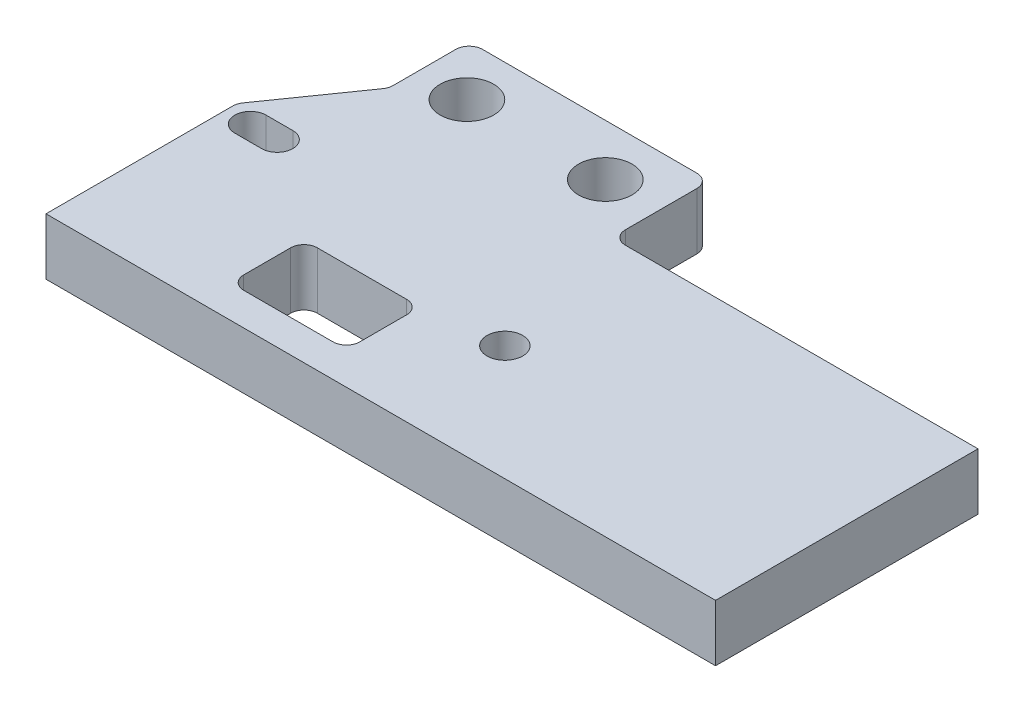
SolidWorks part; units mm, degrees
material "1060 Alloy"
ref_plane "Front Plane" through (0, 0, 0) normal (0, 0, 1) x (1, 0, 0)
ref_plane "Top Plane" through (0, 0, 0) normal (0, 1, 0) x (1, 0, 0)
ref_plane "Right Plane" through (0, 0, 0) normal (1, 0, 0) x (0, 0, -1)
sketch "Sketch1" plane through (0, 0, 0) normal (0, 1, 0) x (1, 0, 0)
  line L0 (38, 0) -> (38, 5)
  line L1 (0, 0) -> (38, 0)
  line L2 (0, 0) -> (0, 48.5)
  line L3 (7, 67.5) -> (34, 67.5)
  line L4 (96, 0) -> (96, 48.5)
  line L5 (0, 48.5) -> (7, 58.5)
  line L6 (7, 58.5) -> (7, 67.5)
  line L7 (34, 67.5) -> (34, 56.5)
  line L8 (48, -139.8616) -> (48, 139.8616) construction
  line L9 (58, 0) -> (58, 5)
  line L10 (96, 48.5) -> (89, 58.5)
  line L11 (89, 58.5) -> (89, 67.5)
  line L12 (62, 67.5) -> (62, 56.5)
  line L13 (38, 5) -> (58, 5)
  line L14 (58, 0) -> (96, 0)
  line L15 (34, 56.5) -> (62, 56.5)
  line L16 (62, 67.5) -> (89, 67.5)
  line L17 (79, 14.5) -> (66, 14.5)
  line L18 (17, 39) -> (30, 39)
  line L19 (17, 39) -> (17, 30.75)
  line L20 (17, 30.75) -> (30, 30.75)
  line L21 (30, 39) -> (30, 30.75)
  line L22 (17, 22.75) -> (30, 22.75)
  line L23 (17, 22.75) -> (17, 14.5)
  line L24 (17, 14.5) -> (30, 14.5)
  line L25 (30, 22.75) -> (30, 14.5)
  line L26 (66, 22.75) -> (66, 14.5)
  line L27 (79, 22.75) -> (66, 22.75)
  line L28 (79, 22.75) -> (79, 14.5)
  line L29 (79, 30.75) -> (66, 30.75)
  line L30 (66, 39) -> (66, 30.75)
  line L31 (79, 39) -> (66, 39)
  line L32 (79, 39) -> (79, 30.75)
  line L33 (2.75, 11.75) -> (5.75, 11.75)
  line L34 (2.75, 8.25) -> (5.75, 8.25)
  line L35 (93.25, 8.25) -> (90.25, 8.25)
  line L36 (93.25, 11.75) -> (90.25, 11.75)
  line L37 (-107.8769, 28.625) -> (107.8769, 28.625) construction
  line L38 (93.25, 45.5) -> (90.25, 45.5)
  line L39 (93.25, 49) -> (90.25, 49)
  line L40 (2.75, 49) -> (5.75, 49)
  line L41 (2.75, 45.5) -> (5.75, 45.5)
  circle A0 centre (38.5, 40) radius 2
  circle A1 centre (38.5, 22) radius 2
  circle A2 centre (57.5, 22) radius 2
  circle A3 centre (57.5, 40) radius 2
  arc A4 (2.75, 11.75) -> (2.75, 8.25) centre (2.75, 10) ccw
  arc A5 (5.75, 8.25) -> (5.75, 11.75) centre (5.75, 10) ccw
  arc A6 (93.25, 11.75) -> (93.25, 8.25) centre (93.25, 10) cw
  arc A7 (90.25, 8.25) -> (90.25, 11.75) centre (90.25, 10) cw
  arc A8 (93.25, 45.5) -> (93.25, 49) centre (93.25, 47.25) ccw
  arc A9 (90.25, 49) -> (90.25, 45.5) centre (90.25, 47.25) ccw
  arc A10 (2.75, 45.5) -> (2.75, 49) centre (2.75, 47.25) cw
  arc A11 (5.75, 49) -> (5.75, 45.5) centre (5.75, 47.25) cw
  circle A12 centre (12.5, 61.75) radius 3
  circle A13 centre (28, 61.75) radius 3
  circle A14 centre (68, 61.75) radius 3
  circle A15 centre (83.5, 61.75) radius 3
  point P14 (48, 0)
  point P59 (0, 28.625)
  dimension "D18" = 4
  dimension "D22" = 3.5
  dimension "D23" = 10
  dimension "D24" = 2.75
  dimension "D25" = 3.5
  dimension "D28" = 6
  dimension "D29" = 5.75
  dimension "D31" = 15.5
  dimension "D1" = 96
  dimension "D2" = 27
  dimension "D3" = 38
  dimension "D4" = 5
  dimension "D5" = 19
  dimension "D6" = 7
  dimension "D7" = 10
  dimension "D8" = 11
  dimension "D9" = 67.5
  dimension "D10" = 8.25
  dimension "D11" = 8.25
  dimension "D12" = 13
  dimension "D13" = 13
  dimension "D14" = 17
  dimension "D15" = 17
  dimension "D16" = 14.5
  dimension "D17" = 8
  dimension "D19" = 16.5
  dimension "D20" = 8.5
  dimension "D21" = 18
  dimension "D26" = 3
  dimension "D27" = 18.625
  dimension "D30" = 5.5
extrude "Boss-Extrude1" add sketch "Sketch1" along normal blind 6.35
fillet "Fillet1" radius 1.5 32 edges at (17, 3.175, -30.75) (17, 3.175, -14.5) (17, 3.175, -22.75) (17, 3.175, -39) (66, 3.175, -22.75) (66, 3.175, -39) (66, 3.175, -30.75) (66, 3.175, -14.5) (79, 3.175, -14.5) (79, 3.175, -30.75) (79, 3.175, -39) (79, 3.175, -22.75) (30, 3.175, -22.75) (30, 3.175, -14.5) (30, 3.175, -30.75) (30, 3.175, -39) (38, 3.175, -5) (58, 3.175, -5) (96, 3.175, -48.5) (89, 3.175, -58.5) (89, 3.175, -67.5) (62, 3.175, -67.5) (62, 3.175, -56.5) (34, 3.175, -56.5) (34, 3.175, -67.5) (7, 3.175, -67.5) (7, 3.175, -58.5) (0, 3.175, -48.5) (0, 3.175, 0) (96, 3.175, 0) (58, 3.175, 0) (38, 3.175, 0)
ref_plane "Plane1" through (48, 0, 0) normal (1, 0, 0) x (0, 0, -1)
sketch "Sketch2" plane through (48, 0, 0) normal (1, 0, 0) x (0, 0, -1)
  line L1 (-7.8701, 8.545) -> (74.4577, 8.545)
  line L2 (-7.8701, 8.545) -> (-7.8701, -5.9133)
  line L3 (-7.8701, -5.9133) -> (74.4577, -5.9133)
  line L4 (74.4577, 8.545) -> (74.4577, -5.9133)
extrude "Cut-Extrude1" cut sketch "Sketch2" along normal blind 51
sketch "Sketch3" plane through (48, 0, 0) normal (1, 0, 0) x (0, 0, -1)
  line L4 (5, 6.35) -> (5, 0)
  line L5 (5, 0) -> (56.5, 0)
  line L6 (56.5, 0) -> (56.5, 6.35)
  line L7 (56.5, 6.35) -> (5, 6.35)
  line L8 (5, 6.35) -> (5, 0)
  line L9 (5, 0) -> (56.5, 0)
  line L10 (56.5, 0) -> (56.5, 6.35)
  line L11 (56.5, 6.35) -> (5, 6.35)
  dimension "D1" = 0
extrude "Boss-Extrude2" add sketch "Sketch3" along normal blind 25
mirror "Mirror1" about plane through (73, 0, 0) normal (1, 0, 0) of bodies 103
ref_plane "Plane2" through (75, 0, 0) normal (1, 0, 0) x (0, 0, -1)
sketch "Sketch4" plane through (75, 0, 0) normal (1, 0, 0) x (0, 0, -1)
  line L1 (-8.4347, 14.082) -> (76.4943, 14.082)
  line L2 (-8.4347, 14.082) -> (-8.4347, -11.8039)
  line L3 (-8.4347, -11.8039) -> (76.4943, -11.8039)
  line L4 (76.4943, 14.082) -> (76.4943, -11.8039)
extrude "Cut-Extrude2" cut sketch "Sketch4" along normal blind 90
sketch "Sketch5" plane through (75, 0, 0) normal (1, 0, 0) x (0, 0, -1)
  line L0 (27, 6.35) -> (27, 0)
  line L1 (56.5, 6.35) -> (5, 6.35) construction
  line L2 (56.5, 0) -> (5, 0) construction
  line L3 (5, 6.35) -> (5, 0) construction
  line L4 (27, 6.35) -> (27.1, 6.35)
  line L5 (27.1, 6.35) -> (27.1, 0)
  line L6 (27.1, 0) -> (27, 0)
  dimension "D1" = 22
  dimension "D2" = 0.1
extrude "Cut-Extrude3" cut sketch "Sketch5" against normal blind 90
sketch "Sketch6" plane through (0, 0, -27) normal (0, 0, -1) x (-1, 0, 0)
  line L1 (-76.5488, 12.2353) -> (4.6965, 12.2353)
  line L2 (-76.5488, 12.2353) -> (-76.5488, -8.7778)
  line L3 (-76.5488, -8.7778) -> (4.6965, -8.7778)
  line L4 (4.6965, 12.2353) -> (4.6965, -8.7778)
extrude "Cut-Extrude4" cut sketch "Sketch6" against normal blind 90
